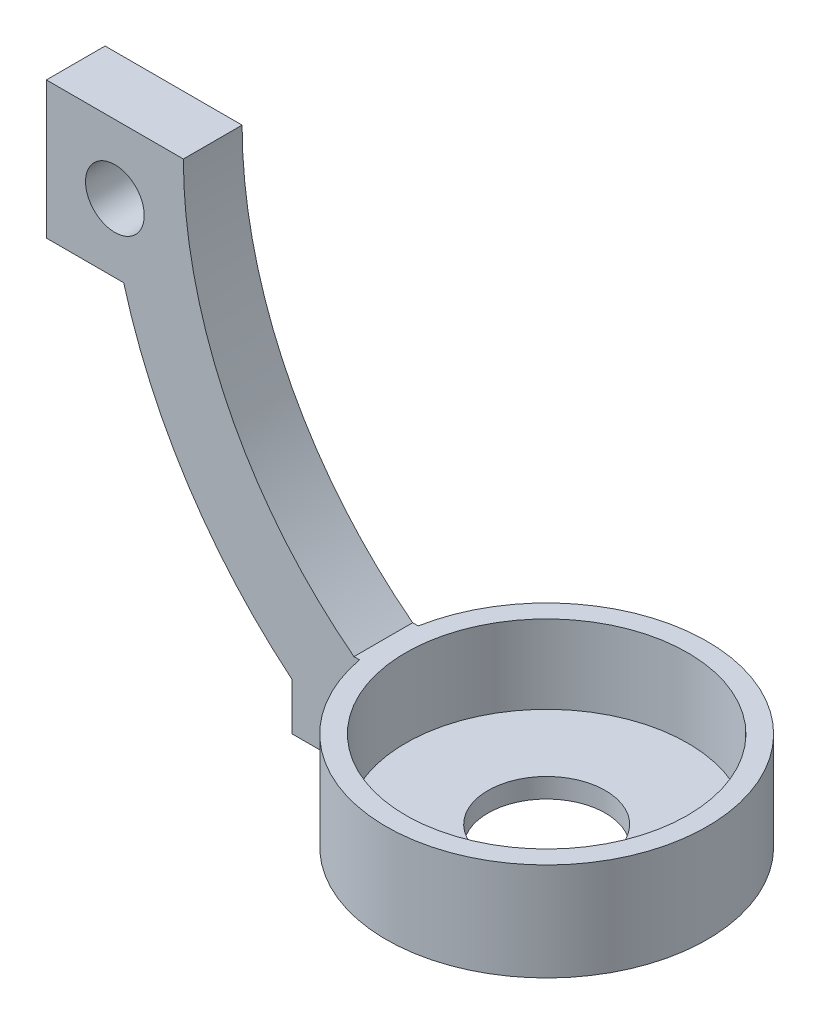
SolidWorks part; units mm, degrees
ref_plane "Front Plane" through (0, 0, 0) normal (0, 0, 1) x (1, 0, 0)
ref_plane "Top Plane" through (0, 0, 0) normal (0, 1, 0) x (1, 0, 0)
ref_plane "Right Plane" through (0, 0, 0) normal (1, 0, 0) x (0, 0, -1)
sketch "Sketch1" plane through (0, 0, 0) normal (0, 0, 1) x (1, 0, 0)
  line L0 (-4.1, 0) -> (4.1, 0) construction
  line L1 (0, 0) -> (0, 2.5) construction
  line L2 (0, 2.5) -> (1.5, 2.5) construction
  line L3 (4.1, 0) -> (4.1, 2.5)
  line L4 (4.1, 2.5) -> (3.6, 2.5)
  line L5 (3.6, 2.5) -> (3.6, 0.5)
  line L6 (3.6, 0.5) -> (1.5, 0.5)
  line L7 (1.5, 0.5) -> (1.5, 0)
  line L8 (1.5, 0) -> (4.1, 0)
  point P4 (0, 0)
  dimension "D2" = 1.5
  dimension "D3" = 0.5
  dimension "D4" = 0.5
  dimension "D5" = 2
  dimension "D1" = 8.2
revolve "Revolve1" add sketch "Sketch1" angle 360 about L1
sketch "Sketch2" plane through (0, 0, 0) normal (0, -1, 0) x (1, 0, 0)
  point P0 (0.2198, -0.6073)
sketch "Sketch3" plane through (0, 0, 0) normal (0, -1, 0) x (1, 0, 0)
  line L0 (0, -4.1) -> (0, 4.1) construction
  line L1 (-2.8991, 2.8991) -> (2.8991, 2.8991) construction
  line L2 (-2.8991, 2.8991) -> (-2.8991, -2.8991) construction
  line L3 (-2.8991, -2.8991) -> (2.8991, -2.8991) construction
  line L4 (2.8991, 2.8991) -> (2.8991, -2.8991) construction
  line L5 (-2.8991, 2.8991) -> (2.8991, -2.8991) construction
  line L6 (-2.8991, -2.8991) -> (2.8991, 2.8991) construction
  line L7 (-4.3246, 0) -> (-5.75, 0) construction
  line L8 (-2.8991, -0.75) -> (-5.75, -0.75)
  line L9 (-2.8991, -0.75) -> (-2.8991, 0.75)
  line L10 (-2.8991, 0.75) -> (-5.75, 0.75)
  line L11 (-5.75, -0.75) -> (-5.75, 0.75)
  line L12 (-2.8991, -0.75) -> (-5.75, 0.75) construction
  line L13 (-2.8991, 0.75) -> (-5.75, -0.75) construction
  line L14 (-4.3246, 0) -> (0, 0) construction
  circle A0 centre (0, 0) radius 4.1 construction
  point P0 (0, 0)
  point P6 (-4.3246, 0)
  point P11 (0, 0)
  dimension "D2" = 1.5
  dimension "D1" = 5.7983
  dimension "D3" = 0
  dimension "D4" = 5.75
ref_plane "Plane1" through (0, 0, -0.75) normal (0, 0, 1) x (1, 0, 0)
sketch "Sketch4" plane through (0, 0, -0.75) normal (0, 0, 1) x (1, 0, 0)
  line L0 (-2.8991, 0) -> (-5.75, 0) construction
  line L1 (-4.1, 0) -> (4.1, 0) construction
  line L2 (-4.0308, 0) -> (-10.5308, 0) construction
  line L3 (-10.5308, 0) -> (-10.5308, 11.33) construction
  line L4 (-4.1728, 2.5) -> (-4.0308, 0)
  line L5 (4.1, 2.5) -> (-4.1, 2.5) construction
  line L6 (-8.5308, 11.33) -> (-10.5308, 11.33)
  line L7 (-10.5308, 11.33) -> (-10.5308, 7.83)
  line L8 (-10.5308, 7.83) -> (-7.9659, 7.83)
  line L9 (-12.0308, 9.58) -> (-8.5308, 9.58) construction
  line L14 (-12.0308, 11.33) -> (-10.5308, 11.33)
  line L15 (-12.0308, 11.33) -> (-12.0308, 7.83)
  line L16 (-12.0308, 7.83) -> (-10.5308, 7.83)
  line L17 (-10.5308, 11.33) -> (-10.5308, 7.83)
  line L18 (-12.0308, 11.33) -> (-10.5308, 7.83) construction
  line L19 (-12.0308, 7.83) -> (-10.5308, 11.33) construction
  line L20 (-8.5308, 11.33) -> (-8.5308, 7.83) construction
  arc A0 (-4.0308, 0) -> (-10.5308, 11.33) centre (2.5937, 11.33) cw
  arc A1 (-3.0213, 1.7265) -> (-8.5308, 11.33) centre (2.5937, 11.33) cw
  circle A2 centre (-10.2808, 9.58) radius 0.75
  point P3 (-11.2808, 9.58)
  dimension "D7" = 1.5
  dimension "D4" = 3.5
  dimension "D5" = 3.5
  dimension "D6" = 1.75
  dimension "D1" = 6.5
  dimension "D2" = 7.08
  dimension "D3" = 2
extrude "Boss-Extrude1" add sketch "Sketch4" along normal blind 1.5 separate body contours L4 A1 L8 A0 | A2 A0 L8 A1 L6 | A2 A0 L7 | A2 L7 L8 A0 | A2 L7 L14 L15 L16
extrude "Boss-Extrude2" add sketch "Sketch3" against normal up to surface (2.5 mm away) up to face at (3.6, 2.5, 0)
sketch "Sketch5" plane through (0, 2.5, 0) normal (0, 1, 0) x (1, 0, 0)
  circle A0 centre (0, 0) radius 3.6
  arc A1 (-3.521, -0.75) -> (-3.521, 0.75) centre (0, 0) ccw construction
  arc A2 (-3.521, -0.75) -> (-3.521, 0.75) centre (0, 0) ccw construction
extrude "Cut-Extrude1" cut sketch "Sketch5" along a picked direction on the side against the normal blind 2 contours A0
equation "\"D1@Sketch1\"=7.2+(0.5*2)"
equation "\"D1@Sketch3\"=sqr(2*(8.2/2)^2)"
equation "\"D6@Sketch4\"=3.5/2"
equation "\"D1@Sketch4\"=4.50+2"
equation "\"D2@Sketch4\"=8.16-1.66+0.58"
